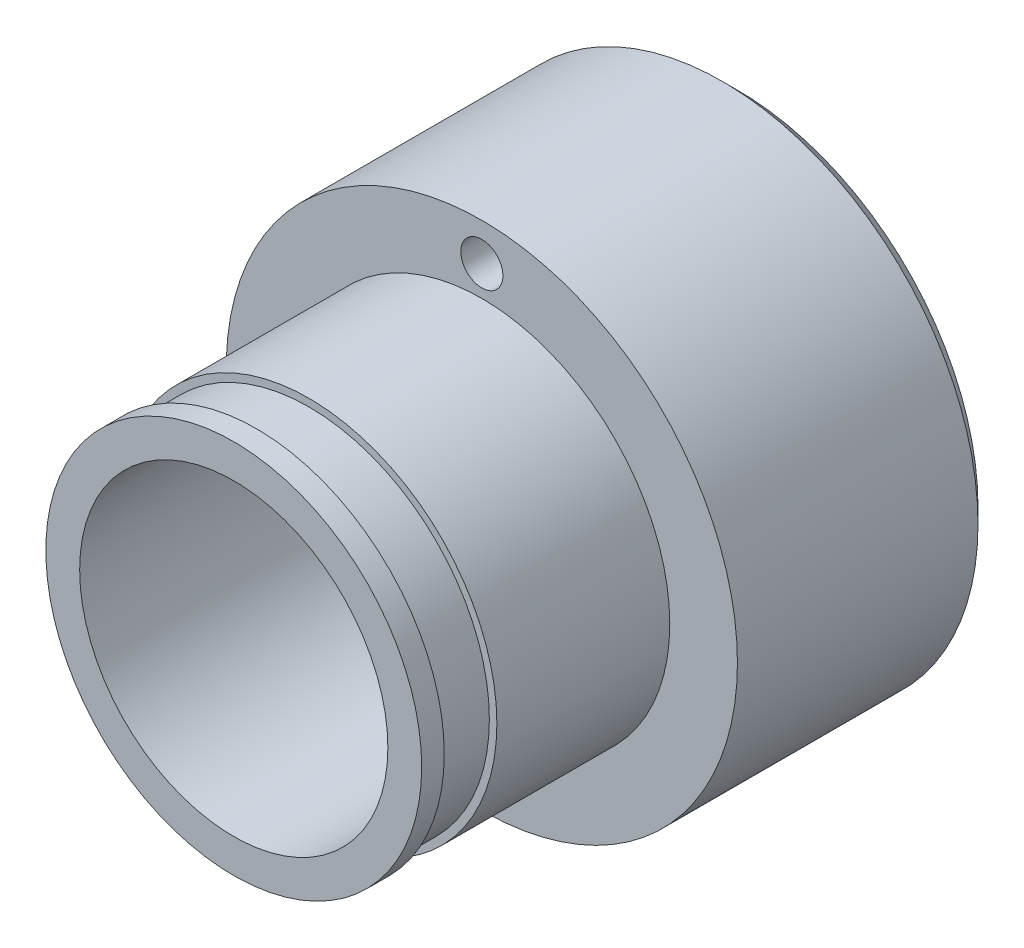
SolidWorks part; units mm, degrees
material "Porcelaine céramique"
ref_plane "Plan de face" through (0, 0, 0) normal (0, 0, 1) x (1, 0, 0)
ref_plane "Plan de dessus" through (0, 0, 0) normal (0, 1, 0) x (1, 0, 0)
ref_plane "Plan de droite" through (0, 0, 0) normal (1, 0, 0) x (0, 0, -1)
sketch "Esquisse1" plane through (0, 0, 0) normal (0, 0, 1) x (1, 0, 0)
  circle A0 centre (0, 0) radius 17
  dimension "D1" = 34
extrude "Boss.-Extru.1" add sketch "Esquisse1" along normal blind 17
sketch "Esquisse2" plane through (0, 0, 17) normal (0, 0, 1) x (1, 0, 0)
  circle A0 centre (0, 0) radius 12.5
  dimension "D1" = 25
extrude "Boss.-Extru.2" add sketch "Esquisse2" along normal blind 11.5
sketch "Esquisse3" plane through (0, 0, 28.5) normal (0, 0, 1) x (1, 0, 0)
  circle A0 centre (0, 0) radius 12
  dimension "D1" = 24
extrude "Boss.-Extru.3" add sketch "Esquisse3" along normal blind 3.5
sketch "Esquisse4" plane through (0, 0, 32) normal (0, 0, 1) x (1, 0, 0)
  circle A0 centre (0, 0) radius 12.5
  dimension "D1" = 25
extrude "Boss.-Extru.4" add sketch "Esquisse4" along normal blind 1.5
sketch "Esquisse5" plane through (0, 0, 33.5) normal (0, 0, 1) x (1, 0, 0)
  circle A0 centre (0, 0) radius 10.25
  dimension "D1" = 20.5
extrude "Enlèv. mat.-Extru.1" cut sketch "Esquisse5" against normal blind 30
cosmetic thread "Représentation de filetage1" parameters "D1"=28, "D2"=21.5
sketch "Esquisse6" plane through (0, 0, 3.5) normal (0, 0, 1) x (1, 0, 0)
  circle A0 centre (0, 0) radius 10.25
  circle A1 centre (0, 0) radius 6.75
  dimension "D1" = 20.5
  dimension "D2" = 13.5
extrude "Enlèv. mat.-Extru.2" cut sketch "Esquisse6" against normal blind 1.5
sketch "Esquisse7" plane through (0, 0, 3.5) normal (0, 0, 1) x (1, 0, 0)
  circle A0 centre (0, 0) radius 12
  circle A1 centre (0, 0) radius 10.25
  dimension "D1" = 24
  dimension "D2" = 20.5
extrude "Enlèv. mat.-Extru.3" cut sketch "Esquisse7" along normal blind 2
hole_wizard "Ø2.8 (2.8) Diameter Hole1" positions "Esquisse9" profile "Esquisse8" hole size "Ø2.8" standard "ISO"
sketch "Esquisse9" plane through (0, 0, 17) normal (0, 0, 1) x (1, 0, 0)
  line L0 (0, 0) -> (0, 14.5) construction
  point P5 (0, 14.5)
  point P10 (0, 14.5)
  dimension "D1" = 14.5
sketch "Esquisse8" plane through (0, 14.5, 17) normal (1, 0, 0) x (0, -1, 0)
  line L0 (0, 0) -> (0, 12.8412)
  line L1 (0, 12.8412) -> (1.4, 12)
  line L2 (1.4, 12) -> (1.4, 0)
  line L5 (1.4, 0) -> (0, 0)
  line L10 (0, 12.8412) -> (-1.4, 12) construction
  line L11 (0, -6.35) -> (0, 107.95) construction
  dimension "Diamètre du perçage" = 2.8
  dimension "Profondeur du perçage" = 12
  dimension "Angle de pointe" = 118
chamfer "Chanfrein1" distance 1 angle 45 1 edges at (17, 0, 0)
